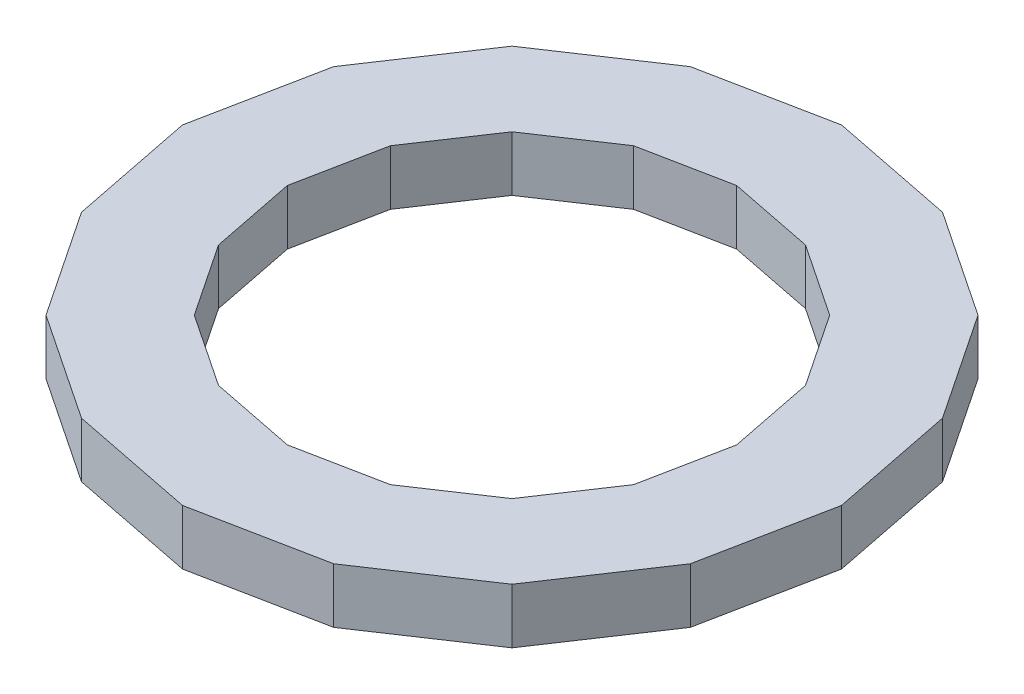
SolidWorks part; units mm, degrees
ref_plane "Front Plane" through (0, 0, 0) normal (0, 0, 1) x (1, 0, 0)
ref_plane "Top Plane" through (0, 0, 0) normal (0, 1, 0) x (1, 0, 0)
ref_plane "Right Plane" through (0, 0, 0) normal (1, 0, 0) x (0, 0, -1)
sketch "Sketch1" plane through (0, 0, 0) normal (0, 1, 0) x (1, 0, 0)
  line L1 (77.6649, 0) -> (71.753, 29.7211)
  line L2 (71.753, 29.7211) -> (54.9174, 54.9174)
  line L3 (54.9174, 54.9174) -> (29.7211, 71.753)
  line L4 (29.7211, 71.753) -> (0, 77.6649)
  line L5 (0, 77.6649) -> (-29.7211, 71.753)
  line L6 (-29.7211, 71.753) -> (-54.9174, 54.9174)
  line L7 (-54.9174, 54.9174) -> (-71.753, 29.7211)
  line L8 (-71.753, 29.7211) -> (-77.6649, 0)
  line L9 (-77.6649, 0) -> (-71.753, -29.7211)
  line L10 (-71.753, -29.7211) -> (-54.9174, -54.9174)
  line L11 (-54.9174, -54.9174) -> (-29.7211, -71.753)
  line L12 (-29.7211, -71.753) -> (0, -77.6649)
  line L13 (0, -77.6649) -> (29.7211, -71.753)
  line L14 (29.7211, -71.753) -> (54.9174, -54.9174)
  line L15 (54.9174, -54.9174) -> (71.753, -29.7211)
  line L16 (71.753, -29.7211) -> (77.6649, 0)
  line L17 (113.9216, 0) -> (105.2498, 43.5959)
  line L18 (105.2498, 43.5959) -> (80.5547, 80.5547)
  line L19 (80.5547, 80.5547) -> (43.5959, 105.2498)
  line L20 (43.5959, 105.2498) -> (0, 113.9216)
  line L21 (0, 113.9216) -> (-43.5959, 105.2498)
  line L22 (-43.5959, 105.2498) -> (-80.5547, 80.5547)
  line L23 (-80.5547, 80.5547) -> (-105.2498, 43.5959)
  line L24 (-105.2498, 43.5959) -> (-113.9216, 0)
  line L25 (-113.9216, 0) -> (-105.2498, -43.5959)
  line L26 (-105.2498, -43.5959) -> (-80.5547, -80.5547)
  line L27 (-80.5547, -80.5547) -> (-43.5959, -105.2498)
  line L28 (-43.5959, -105.2498) -> (0, -113.9216)
  line L29 (0, -113.9216) -> (43.5959, -105.2498)
  line L30 (43.5959, -105.2498) -> (80.5547, -80.5547)
  line L31 (80.5547, -80.5547) -> (105.2498, -43.5959)
  line L32 (105.2498, -43.5959) -> (113.9216, 0)
  circle A1 centre (0, 0) radius 76.1726 construction
  circle A2 centre (0, 0) radius 111.7326 construction
  dimension "D1" = 35.56
  dimension "D2" = 44.45
extrude "Boss-Extrude1" add sketch "Sketch1" along normal blind 19.05
